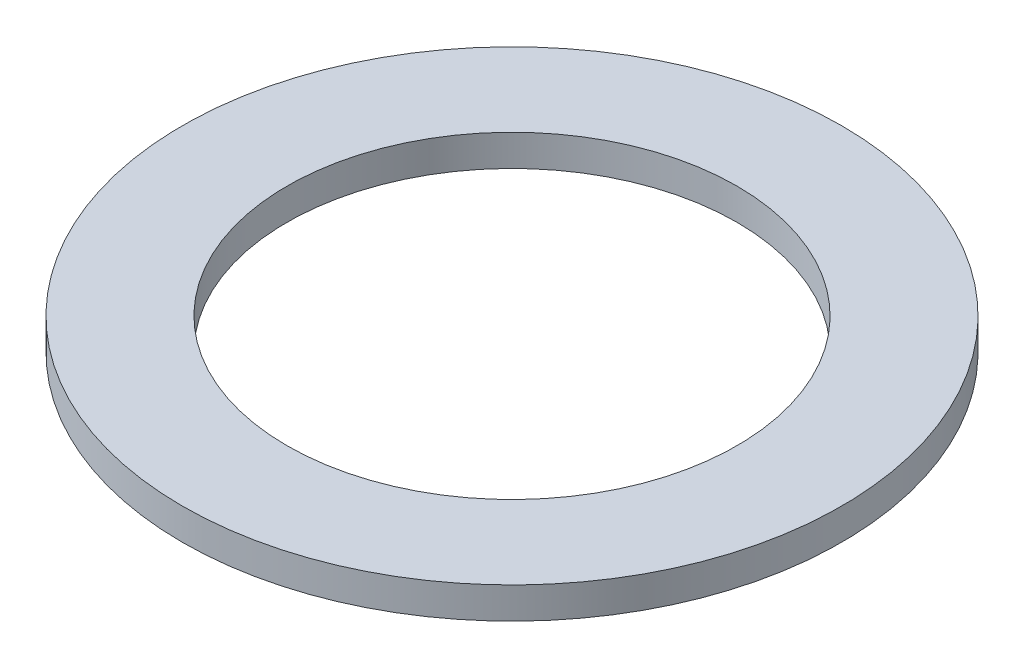
SolidWorks part; units mm, degrees
ref_plane "Front Plane" through (0, 0, 0) normal (0, 0, 1) x (1, 0, 0)
ref_plane "Top Plane" through (0, 0, 0) normal (0, 1, 0) x (1, 0, 0)
ref_plane "Right Plane" through (0, 0, 0) normal (1, 0, 0) x (0, 0, -1)
sketch "Sketch1" plane through (0, 0, 0) normal (0, 1, 0) x (1, 0, 0)
  circle A0 centre (0, 0) radius 21.5
  circle A1 centre (0, 0) radius 31.5
  dimension "D1" = 43
  dimension "D2" = 63
extrude "Boss-Extrude1" add sketch "Sketch1" along normal blind 3 contours A1 A0
equation "\"M3 Nut Diameter\" = 5.50mm"
equation "\"Clearance Diameter 3D Printing\" = .20mm"
equation "\"D-Shaft\"= 4mm'D-Shaft diameter"
equation "\"Wheel Axle Diameter\"= 6.8mm'Axle to Connect to Wheel"
equation "\"Wheel Thickness\"= 10mm'Wheel Thickness"
equation "\"M3 Screw Diameter\"= 3.20mm'M3 Screw Diameter already with 3D printing Clearance"
equation "\"Wheel Diameter\"= 60mm"
equation "\"Silicone Tire Width\"= 7mm"
